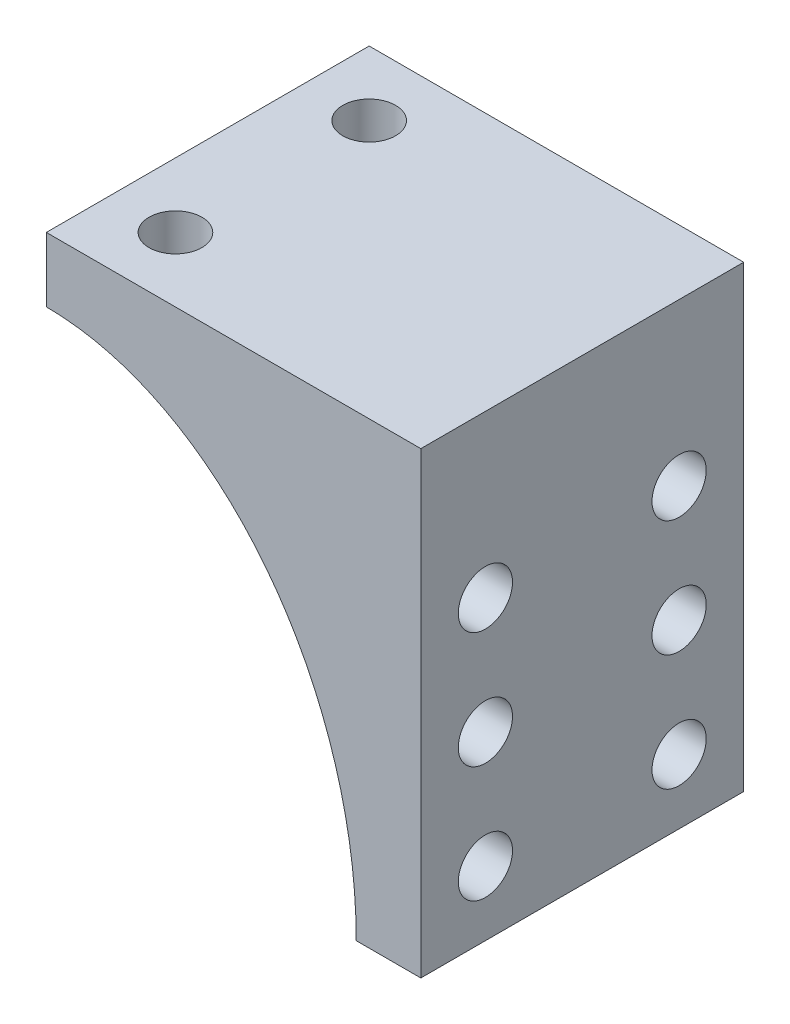
SolidWorks part; units mm, degrees
material "ABS"
ref_plane "前基準面" through (0, 0, 0) normal (0, 0, 1) x (1, 0, 0)
ref_plane "上基準面" through (0, 0, 0) normal (0, 1, 0) x (1, 0, 0)
ref_plane "右基準面" through (0, 0, 0) normal (1, 0, 0) x (0, 0, -1)
sketch "草圖1" plane through (0, 0, 0) normal (0, 0, 1) x (1, 0, 0)
  line L1 (-8.2523, 16.0565) -> (-3.2523, 16.0565)
  line L2 (-8.2523, 16.0565) -> (-8.2523, -19.4435)
  line L3 (-8.2523, -19.4435) -> (-3.2523, -19.4435)
  line L4 (-3.2523, 16.0565) -> (-3.2523, -19.4435)
  line L5 (-3.2523, 16.0565) -> (-32.2523, 16.0565)
  line L6 (-3.2523, 16.0565) -> (-3.2523, 11.0565)
  line L7 (-3.2523, 11.0565) -> (-32.2523, 11.0565)
  line L8 (-32.2523, 16.0565) -> (-32.2523, 11.0565)
  ellipse E0 centre (-32.2523, -19.4435) end of major axis (-32.2523, 11.0565) minor radius 24
  dimension "D1" = 35.5
  dimension "D2" = 5
  dimension "D3" = 5
  dimension "D4" = 29
extrude "填料-伸長1" add sketch "草圖1" along normal blind 25 contours E0 L2 L7 | L4 L7 L2 L3 | L5 L8 L7 L2
sketch "草圖2" plane through (-3.2523, 0, 0) normal (1, 0, 0) x (0, 0, -1)
  line L0 (-25, 16.0565) -> (-25, -19.4435) construction
  line L1 (-25, -19.4435) -> (0, -19.4435) construction
  circle A0 centre (-20, -14.4435) radius 2.1
  circle A1 centre (-5, -14.4435) radius 2.1
  circle A2 centre (-5, -5.4435) radius 2.1
  circle A3 centre (-5, 3.5565) radius 2.1
  circle A4 centre (-20, -5.4435) radius 2.1
  circle A5 centre (-20, 3.5565) radius 2.1
  dimension "D1" = 4.2
  dimension "D2" = 5
  dimension "D3" = 5
  dimension "D4" = 2
  dimension "D5" = 3
extrude "除料-伸長1" cut sketch "草圖2" against normal blind 25
sketch "草圖4" plane through (-32.2523, 0, 0) normal (-1, 0, 0) x (0, 0, 1)
  circle A0 centre (5, 3.5565) radius 4
  circle A1 centre (20, 3.5565) radius 4
  circle A2 centre (20, -5.4435) radius 4
  circle A3 centre (20, -14.4435) radius 4
  circle A4 centre (5, -5.4435) radius 4
  circle A5 centre (5, -14.4435) radius 4
  dimension "D1" = 8
  dimension "D2" = 2
  dimension "D3" = 3
extrude "除料-伸長2" cut sketch "草圖4" against normal blind 24
sketch "草圖5" plane through (0, 16.0565, 0) normal (0, 1, 0) x (1, 0, 0)
  line L0 (-32.2523, -25) -> (-32.2523, 0) construction
  line L1 (-3.2523, 0) -> (-32.2523, 0) construction
  circle A0 centre (-27.2523, -5) radius 2.045
  circle A1 centre (-27.2523, -20) radius 2.045
  dimension "D1" = 5
  dimension "D2" = 5
  dimension "D3" = 2
extrude "除料-伸長3" cut sketch "草圖5" against normal blind 24
sketch "草圖6" plane through (0, -19.4435, 0) normal (0, -1, 0) x (1, 0, 0)
  circle A0 centre (-27.2523, 5) radius 4
  circle A1 centre (-27.2523, 20) radius 4
  dimension "D1" = 8
  dimension "D2" = 8
extrude "除料-伸長4" cut sketch "草圖6" against normal up to vertex (30.5 mm away)
